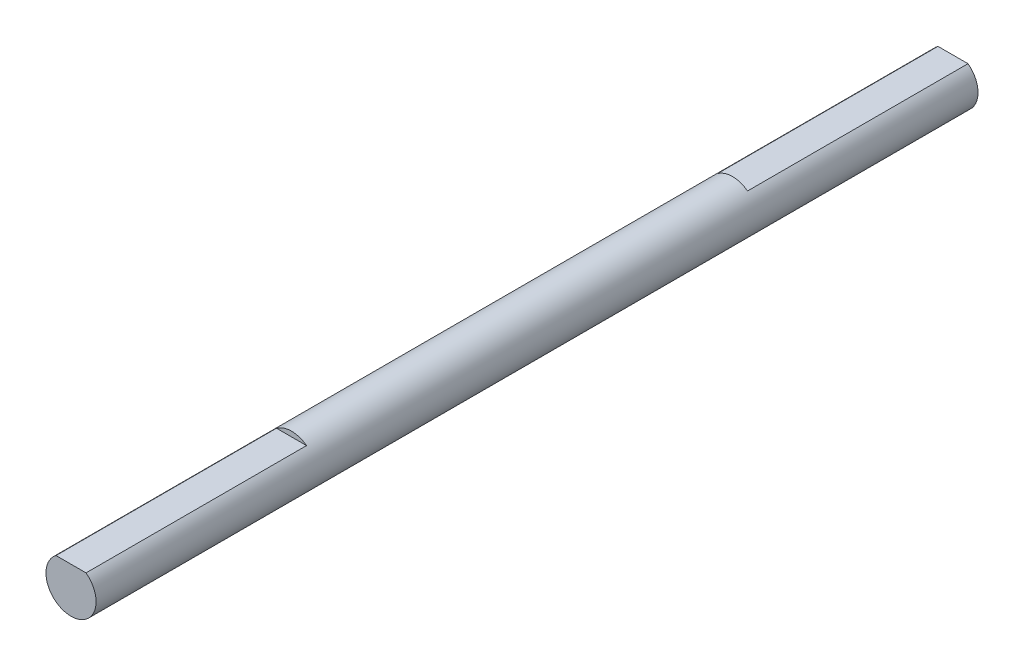
SolidWorks part; units mm, degrees
ref_plane "정면" through (0, 0, 0) normal (0, 0, 1) x (1, 0, 0)
ref_plane "윗면" through (0, 0, 0) normal (0, 1, 0) x (1, 0, 0)
ref_plane "우측면" through (0, 0, 0) normal (1, 0, 0) x (0, 0, -1)
sketch "스케치1" plane through (0, 0, 0) normal (0, 0, 1) x (1, 0, 0)
  circle A0 centre (0, 0) radius 2.5
  dimension "D1" = 5
extrude "보스-돌출1" add sketch "스케치1" along normal blind 88
sketch "스케치2" plane through (0, 0, 0) normal (0, 0, -1) x (-1, 0, 0)
  line L0 (1.5, 2) -> (-1.5, 2)
  line L1 (0, -2.5) -> (2.0339, -2.5) construction
  circle A0 centre (0, 0) radius 2.5 construction
  arc A1 (-1.5, 2) -> (1.5, 2) centre (0, 0) cw
  dimension "D1" = 4.5
extrude "컷-돌출1" cut sketch "스케치2" against normal blind 22
ref_plane "평면1" through (0, 0, 44) normal (0, 0, -1) x (-1, 0, 0)
mirror "대칭 복사1" about plane through (0, 0, 44) normal (0, 0, -1) of "컷-돌출1"
